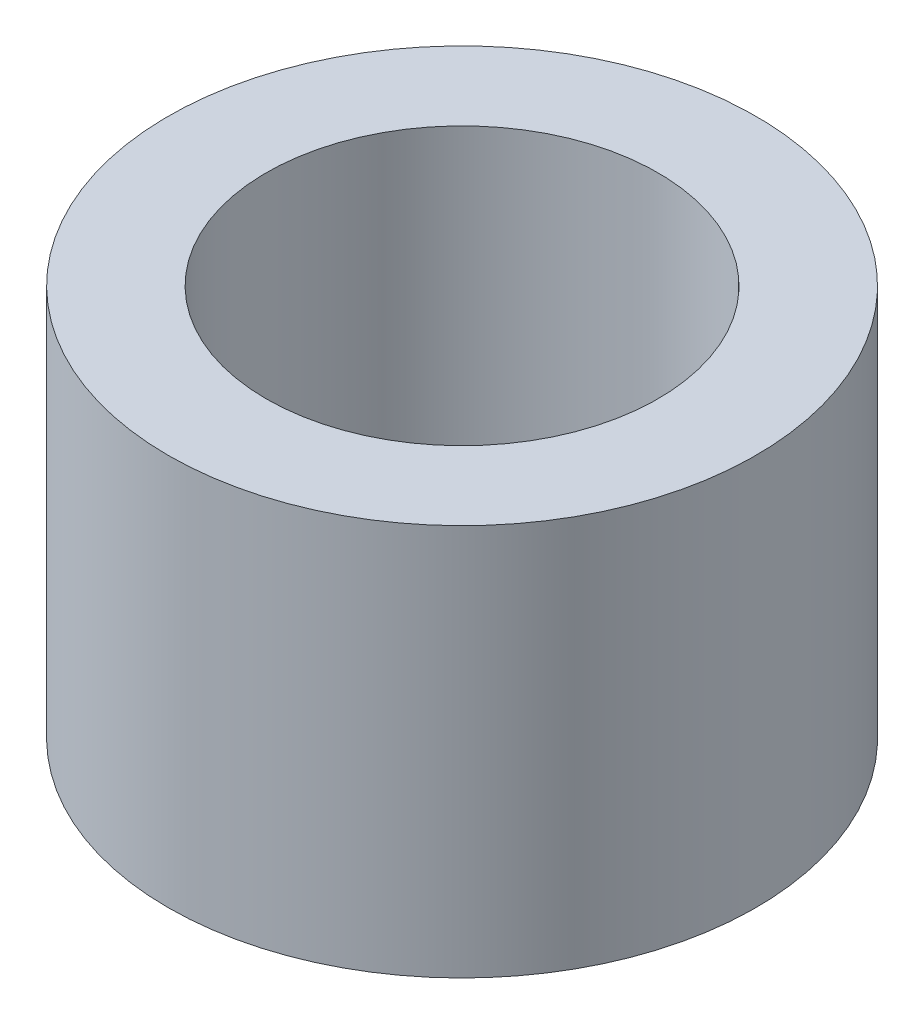
SolidWorks part; units mm, degrees
ref_plane "Plano frontal" through (0, 0, 0) normal (0, 0, 1) x (1, 0, 0)
ref_plane "Plano superior" through (0, 0, 0) normal (0, 1, 0) x (1, 0, 0)
ref_plane "Plano direito" through (0, 0, 0) normal (1, 0, 0) x (0, 0, -1)
sketch "Esboço2" plane through (0, 0, 0) normal (0, 1, 0) x (1, 0, 0)
  circle A0 centre (0, 0) radius 1.5
  circle A1 centre (0, 0) radius 1
  dimension "D1" = 3
  dimension "D2" = 2
extrude "Ressalto-extrusão1" add sketch "Esboço2" along normal blind 2 contours A0 A1
